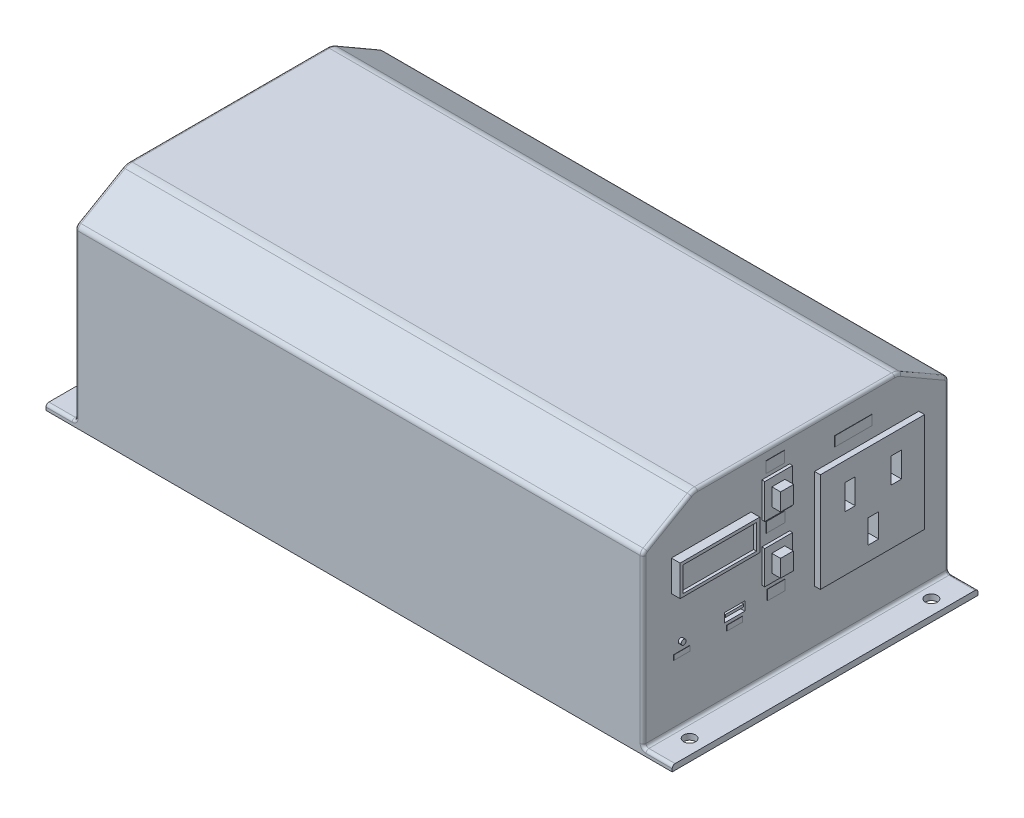
SolidWorks part; units mm, degrees
ref_plane "前视基准面" through (0, 0, 0) normal (0, 0, 1) x (1, 0, 0)
ref_plane "上视基准面" through (0, 0, 0) normal (0, 1, 0) x (1, 0, 0)
ref_plane "右视基准面" through (0, 0, 0) normal (1, 0, 0) x (0, 0, -1)
sketch "草图2" plane through (0, 0, 0) normal (0, 1, 0) x (1, 0, 0)
  line L1 (-107.5, 52.5) -> (107.5, 52.5)
  line L2 (-107.5, 52.5) -> (-107.5, -52.5)
  line L3 (-107.5, -52.5) -> (107.5, -52.5)
  line L4 (107.5, 52.5) -> (107.5, -52.5)
  line L5 (-107.5, 52.5) -> (107.5, -52.5) construction
  line L6 (-107.5, -52.5) -> (107.5, 52.5) construction
  point P0 (0, 0)
  dimension "D1" = 215
  dimension "D2" = 105
extrude "凸台-拉伸1" add sketch "草图2" along normal blind 70
sketch "草图3" plane through (0, 70, 0) normal (0, 1, 0) x (1, 0, 0)
  line L0 (107.5, 52.5) -> (-107.5, 52.5) construction
  line L1 (97.5, 52.5) -> (107.5, 52.5)
  line L2 (97.5, 52.5) -> (97.5, -52.5)
  line L3 (97.5, -52.5) -> (107.5, -52.5)
  line L4 (107.5, 52.5) -> (107.5, -52.5)
  dimension "D1" = 10
extrude "切除-拉伸1" cut sketch "草图3" against normal blind 68 contours L2 L3 L4 L1
sketch "草图4" plane through (0, 70, 0) normal (0, 1, 0) x (1, 0, 0)
  line L0 (-107.5, -52.5) -> (97.5, -52.5) construction
  line L1 (-107.5, 52.5) -> (-97.5, 52.5)
  line L2 (-107.5, 52.5) -> (-107.5, -52.5)
  line L3 (-107.5, -52.5) -> (-97.5, -52.5)
  line L4 (-97.5, 52.5) -> (-97.5, -52.5)
  dimension "D1" = 10
extrude "切除-拉伸2" cut sketch "草图4" against normal blind 68
chamfer "倒角1" distance 10 angle 60 1 edges at (0, 70, 52.5)
chamfer "倒角2" distance 10 angle 60 1 edges at (0, 70, -52.5)
fillet "圆角3" radius 5 1 edges at (0, 70, 35.1795)
fillet "圆角4" radius 5 1 edges at (0, 70, -35.1795)
fillet "圆角7" radius 2 1 edges at (0, 60, 52.5)
fillet "圆角8" radius 2 1 edges at (0, 60, -52.5)
fillet "圆角10" radius 1 12 edges at (102.5, 2, -52.5) (102.5, 2, 52.5) (97.5, 2, 0) (97.5, 30.4226, 52.5) (97.5, 59.8453, 52.2321) (97.5, 64.9537, 43.9199) (97.5, 69.8296, 35.1338) (97.5, 70, 0) (97.5, 69.8296, -35.1338) (97.5, 64.9537, -43.9199) (97.5, 59.8453, -52.2321) (97.5, 30.4226, -52.5)
fillet "圆角11" radius 1 12 edges at (-102.5, 2, 52.5) (-102.5, 2, -52.5) (-97.5, 69.8296, -35.1338) (-97.5, 70, 0) (-97.5, 69.8296, 35.1338) (-97.5, 64.9537, 43.9199) (-97.5, 59.8453, 52.2321) (-97.5, 30.4226, 52.5) (-97.5, 2, 0) (-97.5, 30.4226, -52.5) (-97.5, 59.8453, -52.2321) (-97.5, 64.9537, -43.9199)
sketch "草图6" plane through (0, 2, 0) normal (0, 1, 0) x (1, 0, 0)
  line L0 (107.5, 51.5) -> (98.5, 51.5) construction
  line L1 (107.5, 51.5) -> (107.5, -51.5) construction
  circle A0 centre (102.5, 41.5) radius 2.05
  dimension "D1" = 4.1
  dimension "D2" = 10
  dimension "D3" = 5
extrude "切除-拉伸3" cut sketch "草图6" against normal blind 2
sketch "草图7" plane through (0, 2, 0) normal (0, 1, 0) x (1, 0, 0)
  line L0 (107.5, 51.5) -> (107.5, -51.5) construction
  line L1 (98.5, -51.5) -> (107.5, -51.5) construction
  circle A0 centre (102.5, -41.5125) radius 2.05
  point P4 (103, -51.5)
  dimension "D1" = 4.1
  dimension "D2" = 5
  dimension "D3" = 10
extrude "切除-拉伸4" cut sketch "草图7" against normal blind 2
sketch "草图8" plane through (0, 2, 0) normal (0, 1, 0) x (1, 0, 0)
  line L0 (-98.5, 51.5) -> (-107.5, 51.5) construction
  line L1 (-107.5, 51.5) -> (-107.5, -51.5) construction
  circle A0 centre (-102.5, 41.5) radius 2.05
  dimension "D1" = 4.1
  dimension "D2" = 10
  dimension "D3" = 5
extrude "切除-拉伸5" cut sketch "草图8" against normal blind 2
sketch "草图9" plane through (0, 2, 0) normal (0, 1, 0) x (1, 0, 0)
  line L0 (-107.5, 51.5) -> (-107.5, -51.5) construction
  line L1 (-107.5, -51.5) -> (-98.5, -51.5) construction
  circle A0 centre (-102.5, -41.5) radius 2.05
  dimension "D1" = 4.1
  dimension "D2" = 5
  dimension "D3" = 10
extrude "切除-拉伸6" cut sketch "草图9" against normal blind 2
sketch "草图10" plane through (97.5, 0, 0) normal (1, 0, 0) x (0, 0, -1)
  line L1 (-42.7875, 53.7552) -> (-15.4262, 53.7552)
  line L2 (-42.7875, 53.7552) -> (-42.7875, 43.18)
  line L3 (-42.7875, 43.18) -> (-15.4262, 43.18)
  line L4 (-15.4262, 53.7552) -> (-15.4262, 43.18)
extrude "凸台-拉伸2" add sketch "草图10" along normal blind 3
sketch "草图11" plane through (100.5, 0, 0) normal (1, 0, 0) x (0, 0, -1)
  line L1 (-41.7602, 52.7164) -> (-16.5736, 52.7164)
  line L2 (-41.7602, 52.7164) -> (-41.7602, 44.1809)
  line L3 (-41.7602, 44.1809) -> (-16.5736, 44.1809)
  line L4 (-16.5736, 52.7164) -> (-16.5736, 44.1809)
extrude "切除-拉伸7" cut sketch "草图11" against normal blind 1
sketch "草图13" plane through (97.5, 0, 0) normal (1, 0, 0) x (0, 0, -1)
  line L1 (-11.7222, 61.4568) -> (-2.1798, 61.4568)
  line L2 (-11.7222, 61.4568) -> (-11.7222, 49.5707)
  line L3 (-11.7222, 49.5707) -> (-2.1798, 49.5707)
  line L4 (-2.1798, 61.4568) -> (-2.1798, 49.5707)
  line L5 (-11.7222, 41.535) -> (-2.1798, 41.535)
  line L6 (-11.7222, 41.535) -> (-11.7222, 30.1511)
  line L7 (-11.7222, 30.1511) -> (-2.1798, 30.1511)
  line L8 (-2.1798, 41.535) -> (-2.1798, 30.1511)
extrude "凸台-拉伸3" add sketch "草图13" along normal blind 1
sketch "草图16" plane through (98.5, 0, 0) normal (1, 0, 0) x (0, 0, -1)
  line L1 (-9.2741, 58.6676) -> (-4.781, 58.6676)
  line L2 (-9.2741, 58.6676) -> (-9.2741, 52.6768)
  line L3 (-9.2741, 52.6768) -> (-4.781, 52.6768)
  line L4 (-4.781, 58.6676) -> (-4.781, 52.6768)
extrude "凸台-拉伸5" add sketch "草图16" along normal blind 3
sketch "草图17" plane through (98.5, 0, 0) normal (1, 0, 0) x (0, 0, -1)
  line L1 (-9.2989, 38.92) -> (-4.8823, 38.92)
  line L2 (-9.2989, 38.92) -> (-9.2989, 33.0063)
  line L3 (-9.2989, 33.0063) -> (-4.8823, 33.0063)
  line L4 (-4.8823, 38.92) -> (-4.8823, 33.0063)
extrude "凸台-拉伸6" add sketch "草图17" along normal blind 3
sketch "草图18" plane through (97.5, 0, 0) normal (1, 0, 0) x (0, 0, -1)
  line L1 (-10.3142, 66.4472) -> (-3.9713, 66.4472)
  line L2 (-10.3142, 66.4472) -> (-10.3142, 62.6991)
  line L3 (-10.3142, 62.6991) -> (-3.9713, 62.6991)
  line L4 (-3.9713, 66.4472) -> (-3.9713, 62.6991)
extrude "凸台-拉伸7" add sketch "草图18" along normal blind 0.1
sketch "草图19" plane through (97.5, 0, 0) normal (1, 0, 0) x (0, 0, -1)
  line L1 (-10.2843, 48.3887) -> (-3.927, 48.3887)
  line L2 (-10.2843, 48.3887) -> (-10.2843, 44.8922)
  line L3 (-10.2843, 44.8922) -> (-3.927, 44.8922)
  line L4 (-3.927, 48.3887) -> (-3.927, 44.8922)
extrude "凸台-拉伸8" add sketch "草图19" along normal blind 0.1
sketch "草图20" plane through (97.5, 0, 0) normal (1, 0, 0) x (0, 0, -1)
  line L1 (-9.887, 28.0452) -> (-3.8475, 28.0452)
  line L2 (-9.887, 28.0452) -> (-9.887, 24.6281)
  line L3 (-9.887, 24.6281) -> (-3.8475, 24.6281)
  line L4 (-3.8475, 28.0452) -> (-3.8475, 24.6281)
extrude "凸台-拉伸9" add sketch "草图20" along normal blind 0.1
sketch "草图21" plane through (97.5, 0, 0) normal (1, 0, 0) x (0, 0, -1)
  line L1 (6.3733, 54.9357) -> (42.163, 54.9357)
  line L2 (6.3733, 54.9357) -> (6.3733, 20.8256)
  line L3 (6.3733, 20.8256) -> (42.163, 20.8256)
  line L4 (42.163, 54.9357) -> (42.163, 20.8256)
extrude "凸台-拉伸10" add sketch "草图21" along normal blind 2
sketch "草图23" plane through (99.5, 0, 0) normal (1, 0, 0) x (0, 0, -1)
  line L1 (14.8731, 48.3754) -> (18.3499, 48.3754)
  line L2 (14.8731, 48.3754) -> (14.8731, 39.7205)
  line L3 (14.8731, 39.7205) -> (18.3499, 39.7205)
  line L4 (18.3499, 48.3754) -> (18.3499, 39.7205)
  line L5 (30.7035, 48.3754) -> (34.2543, 48.3754)
  line L6 (30.7035, 48.3754) -> (30.7035, 39.7205)
  line L7 (30.7035, 39.7205) -> (34.2543, 39.7205)
  line L8 (34.2543, 48.3754) -> (34.2543, 39.7205)
  line L9 (22.7883, 33.9505) -> (26.413, 33.9505)
  line L10 (22.7883, 33.9505) -> (22.7883, 25.8134)
  line L11 (22.7883, 25.8134) -> (26.413, 25.8134)
  line L12 (26.413, 33.9505) -> (26.413, 25.8134)
extrude "切除-拉伸9" cut sketch "草图23" against normal blind 20
sketch "草图25" plane through (97.5, 0, 0) normal (1, 0, 0) x (0, 0, -1)
  line L1 (-24.5658, 28.4027) -> (-17.5532, 28.4027)
  line L2 (-24.5658, 28.4027) -> (-24.5658, 27.6834)
  line L3 (-24.5658, 27.6834) -> (-17.5532, 27.6834)
  line L4 (-17.5532, 28.4027) -> (-17.5532, 27.6834)
  line L5 (-24.5658, 26.7844) -> (-17.5532, 26.7844)
  line L6 (-24.5658, 26.7844) -> (-24.5658, 25.3459)
  line L7 (-24.5658, 25.3459) -> (-17.5532, 25.3459)
  line L8 (-17.5532, 26.7844) -> (-17.5532, 25.3459)
extrude "切除-拉伸11" cut sketch "草图25" against normal blind 16
sketch "草图26" plane through (97.5, 0, 0) normal (1, 0, 0) x (0, 0, -1)
  line L0 (-17.5532, 26.7844) -> (-24.5658, 26.7844) construction
  line L1 (-24.5658, 27.6834) -> (-24.1821, 27.6834)
  line L2 (-24.5658, 27.6834) -> (-24.5658, 26.7844)
  line L3 (-24.5658, 26.7844) -> (-24.1821, 26.7844)
  line L4 (-24.1821, 27.6834) -> (-24.1821, 26.7844)
  line L5 (-17.5532, 26.7844) -> (-24.5658, 26.7844) construction
  line L6 (-17.5532, 27.6834) -> (-17.9438, 27.6834)
  line L7 (-17.5532, 27.6834) -> (-17.5532, 26.7844)
  line L8 (-17.5532, 26.7844) -> (-17.9438, 26.7844)
  line L9 (-17.9438, 27.6834) -> (-17.9438, 26.7844)
extrude "切除-拉伸12" cut sketch "草图26" against normal blind 16
sketch "草图27" plane through (97.5, 0, 0) normal (1, 0, 0) x (0, 0, -1)
  line L1 (-23.7895, 24.3135) -> (-18.4371, 24.3135)
  line L2 (-23.7895, 24.3135) -> (-23.7895, 22.5843)
  line L3 (-23.7895, 22.5843) -> (-18.4371, 22.5843)
  line L4 (-18.4371, 24.3135) -> (-18.4371, 22.5843)
extrude "凸台-拉伸11" add sketch "草图27" along normal blind 0.1
sketch "草图28" plane through (97.5, 0, 0) normal (1, 0, 0) x (0, 0, -1)
  circle A0 centre (-39.5486, 27.6152) radius 0.8554
extrude "凸台-拉伸12" add sketch "草图28" along normal blind 1
sketch "草图29" plane through (97.5, 0, 0) normal (1, 0, 0) x (0, 0, -1)
  line L1 (-42.0219, 24.6274) -> (-36.4429, 24.6274)
  line L2 (-42.0219, 24.6274) -> (-42.0219, 22.9744)
  line L3 (-42.0219, 22.9744) -> (-36.4429, 22.9744)
  line L4 (-36.4429, 24.6274) -> (-36.4429, 22.9744)
extrude "凸台-拉伸13" add sketch "草图29" along normal blind 0.1
sketch "草图30" plane through (97.5, 0, 0) normal (1, 0, 0) x (0, 0, -1)
  line L1 (13.3014, 62.1124) -> (26.0771, 62.1124)
  line L2 (13.3014, 62.1124) -> (13.3014, 58.783)
  line L3 (13.3014, 58.783) -> (26.0771, 58.783)
  line L4 (26.0771, 62.1124) -> (26.0771, 58.783)
extrude "凸台-拉伸14" add sketch "草图30" along normal blind 0.1
sketch "草图31" plane through (-97.5, 0, 0) normal (-1, 0, 0) x (0, 0, 1)
  circle A0 centre (-0.808, 48.9903) radius 3.5
  dimension "D1" = 7
extrude "凸台-拉伸15" add sketch "草图31" along normal blind 10
sketch "草图32" plane through (-97.5, 0, 0) normal (-1, 0, 0) x (0, 0, 1)
  circle A0 centre (0, 20.337) radius 3.5
  dimension "D1" = 7
extrude "凸台-拉伸16" add sketch "草图32" along normal blind 10
sketch "草图33" plane through (-97.5, 0, 0) normal (-1, 0, 0) x (0, 0, 1)
  line L1 (-8.7181, 35.5098) -> (6.5852, 35.5098)
  line L2 (-8.7181, 35.5098) -> (-8.7181, 31.3533)
  line L3 (-8.7181, 31.3533) -> (6.5852, 31.3533)
  line L4 (6.5852, 35.5098) -> (6.5852, 31.3533)
extrude "凸台-拉伸17" add sketch "草图33" along normal blind 0.1
sketch "草图34" plane through (-97.5, 0, 0) normal (-1, 0, 0) x (0, 0, 1)
  line L0 (-45.0012, 52.202) -> (-45.0012, 12.6547)
  line L1 (-47.0012, 52.202) -> (-46.1296, 52.202)
  line L2 (-47.0012, 52.202) -> (-47.0012, 12.6547)
  line L3 (-47.0012, 12.6547) -> (-46.1296, 12.6547)
  line L4 (-46.1296, 52.202) -> (-46.1296, 12.6547)
  line L5 (-45.0012, 52.202) -> (-44.1296, 52.202)
  line L6 (-44.1296, 52.202) -> (-44.1296, 12.6547)
  line L7 (-45.0012, 12.6547) -> (-44.1296, 12.6547)
  line L8 (-43.0012, 52.202) -> (-43.0012, 12.6547)
  line L9 (-43.0012, 52.202) -> (-42.1296, 52.202)
  line L10 (-42.1296, 52.202) -> (-42.1296, 12.6547)
  line L11 (-43.0012, 12.6547) -> (-42.1296, 12.6547)
  line L12 (-41.0012, 52.202) -> (-41.0012, 12.6547)
  line L13 (-41.0012, 52.202) -> (-40.1296, 52.202)
  line L14 (-40.1296, 52.202) -> (-40.1296, 12.6547)
  line L15 (-41.0012, 12.6547) -> (-40.1296, 12.6547)
  line L16 (-39.0012, 52.202) -> (-39.0012, 12.6547)
  line L17 (-39.0012, 52.202) -> (-38.1296, 52.202)
  line L18 (-38.1296, 52.202) -> (-38.1296, 12.6547)
  line L19 (-39.0012, 12.6547) -> (-38.1296, 12.6547)
  line L20 (-37.0012, 52.202) -> (-37.0012, 12.6547)
  line L21 (-37.0012, 52.202) -> (-36.1296, 52.202)
  line L22 (-36.1296, 52.202) -> (-36.1296, 12.6547)
  line L23 (-37.0012, 12.6547) -> (-36.1296, 12.6547)
  line L24 (-35.0012, 52.202) -> (-35.0012, 12.6547)
  line L25 (-35.0012, 52.202) -> (-34.1296, 52.202)
  line L26 (-34.1296, 52.202) -> (-34.1296, 12.6547)
  line L27 (-35.0012, 12.6547) -> (-34.1296, 12.6547)
  line L28 (-33.0012, 52.202) -> (-33.0012, 12.6547)
  line L29 (-33.0012, 52.202) -> (-32.1296, 52.202)
  line L30 (-32.1296, 52.202) -> (-32.1296, 12.6547)
  line L31 (-33.0012, 12.6547) -> (-32.1296, 12.6547)
  line L32 (-31.0012, 52.202) -> (-31.0012, 12.6547)
  line L33 (-31.0012, 52.202) -> (-30.1296, 52.202)
  line L34 (-30.1296, 52.202) -> (-30.1296, 12.6547)
  line L35 (-31.0012, 12.6547) -> (-30.1296, 12.6547)
  line L36 (-29.0012, 52.202) -> (-29.0012, 12.6547)
  line L37 (-29.0012, 52.202) -> (-28.1296, 52.202)
  line L38 (-28.1296, 52.202) -> (-28.1296, 12.6547)
  line L39 (-29.0012, 12.6547) -> (-28.1296, 12.6547)
  line L40 (-27.0012, 52.202) -> (-27.0012, 12.6547)
  line L41 (-27.0012, 52.202) -> (-26.1296, 52.202)
  line L42 (-26.1296, 52.202) -> (-26.1296, 12.6547)
  line L43 (-27.0012, 12.6547) -> (-26.1296, 12.6547)
  line L44 (-25.0012, 52.202) -> (-25.0012, 12.6547)
  line L45 (-25.0012, 52.202) -> (-24.1296, 52.202)
  line L46 (-24.1296, 52.202) -> (-24.1296, 12.6547)
  line L47 (-25.0012, 12.6547) -> (-24.1296, 12.6547)
  line L48 (-23.0012, 52.202) -> (-23.0012, 12.6547)
  line L49 (-23.0012, 52.202) -> (-22.1296, 52.202)
  line L50 (-22.1296, 52.202) -> (-22.1296, 12.6547)
  line L51 (-23.0012, 12.6547) -> (-22.1296, 12.6547)
  line L52 (-21.0012, 52.202) -> (-21.0012, 12.6547)
  line L53 (-21.0012, 52.202) -> (-20.1296, 52.202)
  line L54 (-20.1296, 52.202) -> (-20.1296, 12.6547)
  line L55 (-21.0012, 12.6547) -> (-20.1296, 12.6547)
  line L56 (-19.0012, 52.202) -> (-19.0012, 12.6547)
  line L57 (-19.0012, 52.202) -> (-18.1296, 52.202)
  line L58 (-18.1296, 52.202) -> (-18.1296, 12.6547)
  line L59 (-19.0012, 12.6547) -> (-18.1296, 12.6547)
  line L60 (-17.0012, 52.202) -> (-17.0012, 12.6547)
  line L61 (-17.0012, 52.202) -> (-16.1296, 52.202)
  line L62 (-16.1296, 52.202) -> (-16.1296, 12.6547)
  line L63 (-17.0012, 12.6547) -> (-16.1296, 12.6547)
  line L64 (-15.0012, 52.202) -> (-15.0012, 12.6547)
  line L65 (-15.0012, 52.202) -> (-14.1296, 52.202)
  line L66 (-14.1296, 52.202) -> (-14.1296, 12.6547)
  line L67 (-15.0012, 12.6547) -> (-14.1296, 12.6547)
  dimension "D1" = 17
extrude "切除-拉伸13" cut sketch "草图34" against normal blind 10
sketch "草图35" plane through (-97.5, 0, 0) normal (-1, 0, 0) x (0, 0, 1)
  line L0 (16.176, 51.9532) -> (16.176, 12.9281)
  line L1 (14.176, 51.9532) -> (15.0674, 51.9532)
  line L2 (14.176, 51.9532) -> (14.176, 12.9281)
  line L3 (14.176, 12.9281) -> (15.0674, 12.9281)
  line L4 (15.0674, 51.9532) -> (15.0674, 12.9281)
  line L5 (16.176, 51.9532) -> (17.0674, 51.9532)
  line L6 (17.0674, 51.9532) -> (17.0674, 12.9281)
  line L7 (16.176, 12.9281) -> (17.0674, 12.9281)
  line L8 (18.176, 51.9532) -> (18.176, 12.9281)
  line L9 (18.176, 51.9532) -> (19.0674, 51.9532)
  line L10 (19.0674, 51.9532) -> (19.0674, 12.9281)
  line L11 (18.176, 12.9281) -> (19.0674, 12.9281)
  line L12 (20.176, 51.9532) -> (20.176, 12.9281)
  line L13 (20.176, 51.9532) -> (21.0674, 51.9532)
  line L14 (21.0674, 51.9532) -> (21.0674, 12.9281)
  line L15 (20.176, 12.9281) -> (21.0674, 12.9281)
  line L16 (22.176, 51.9532) -> (22.176, 12.9281)
  line L17 (22.176, 51.9532) -> (23.0674, 51.9532)
  line L18 (23.0674, 51.9532) -> (23.0674, 12.9281)
  line L19 (22.176, 12.9281) -> (23.0674, 12.9281)
  line L20 (24.176, 51.9532) -> (24.176, 12.9281)
  line L21 (24.176, 51.9532) -> (25.0674, 51.9532)
  line L22 (25.0674, 51.9532) -> (25.0674, 12.9281)
  line L23 (24.176, 12.9281) -> (25.0674, 12.9281)
  line L24 (26.176, 51.9532) -> (26.176, 12.9281)
  line L25 (26.176, 51.9532) -> (27.0674, 51.9532)
  line L26 (27.0674, 51.9532) -> (27.0674, 12.9281)
  line L27 (26.176, 12.9281) -> (27.0674, 12.9281)
  line L28 (28.176, 51.9532) -> (28.176, 12.9281)
  line L29 (28.176, 51.9532) -> (29.0674, 51.9532)
  line L30 (29.0674, 51.9532) -> (29.0674, 12.9281)
  line L31 (28.176, 12.9281) -> (29.0674, 12.9281)
  line L32 (30.176, 51.9532) -> (30.176, 12.9281)
  line L33 (30.176, 51.9532) -> (31.0674, 51.9532)
  line L34 (31.0674, 51.9532) -> (31.0674, 12.9281)
  line L35 (30.176, 12.9281) -> (31.0674, 12.9281)
  line L36 (32.176, 51.9532) -> (32.176, 12.9281)
  line L37 (32.176, 51.9532) -> (33.0674, 51.9532)
  line L38 (33.0674, 51.9532) -> (33.0674, 12.9281)
  line L39 (32.176, 12.9281) -> (33.0674, 12.9281)
  line L40 (34.176, 51.9532) -> (34.176, 12.9281)
  line L41 (34.176, 51.9532) -> (35.0674, 51.9532)
  line L42 (35.0674, 51.9532) -> (35.0674, 12.9281)
  line L43 (34.176, 12.9281) -> (35.0674, 12.9281)
  line L44 (36.176, 51.9532) -> (36.176, 12.9281)
  line L45 (36.176, 51.9532) -> (37.0674, 51.9532)
  line L46 (37.0674, 51.9532) -> (37.0674, 12.9281)
  line L47 (36.176, 12.9281) -> (37.0674, 12.9281)
  line L48 (38.176, 51.9532) -> (38.176, 12.9281)
  line L49 (38.176, 51.9532) -> (39.0674, 51.9532)
  line L50 (39.0674, 51.9532) -> (39.0674, 12.9281)
  line L51 (38.176, 12.9281) -> (39.0674, 12.9281)
  line L52 (40.176, 51.9532) -> (40.176, 12.9281)
  line L53 (40.176, 51.9532) -> (41.0674, 51.9532)
  line L54 (41.0674, 51.9532) -> (41.0674, 12.9281)
  line L55 (40.176, 12.9281) -> (41.0674, 12.9281)
  line L56 (42.176, 51.9532) -> (42.176, 12.9281)
  line L57 (42.176, 51.9532) -> (43.0674, 51.9532)
  line L58 (43.0674, 51.9532) -> (43.0674, 12.9281)
  line L59 (42.176, 12.9281) -> (43.0674, 12.9281)
  line L60 (44.176, 51.9532) -> (44.176, 12.9281)
  line L61 (44.176, 51.9532) -> (45.0674, 51.9532)
  line L62 (45.0674, 51.9532) -> (45.0674, 12.9281)
  line L63 (44.176, 12.9281) -> (45.0674, 12.9281)
  line L64 (46.176, 51.9532) -> (46.176, 12.9281)
  line L65 (46.176, 51.9532) -> (47.0674, 51.9532)
  line L66 (47.0674, 51.9532) -> (47.0674, 12.9281)
  line L67 (46.176, 12.9281) -> (47.0674, 12.9281)
  dimension "D1" = 17
extrude "切除-拉伸14" cut sketch "草图35" against normal blind 10
